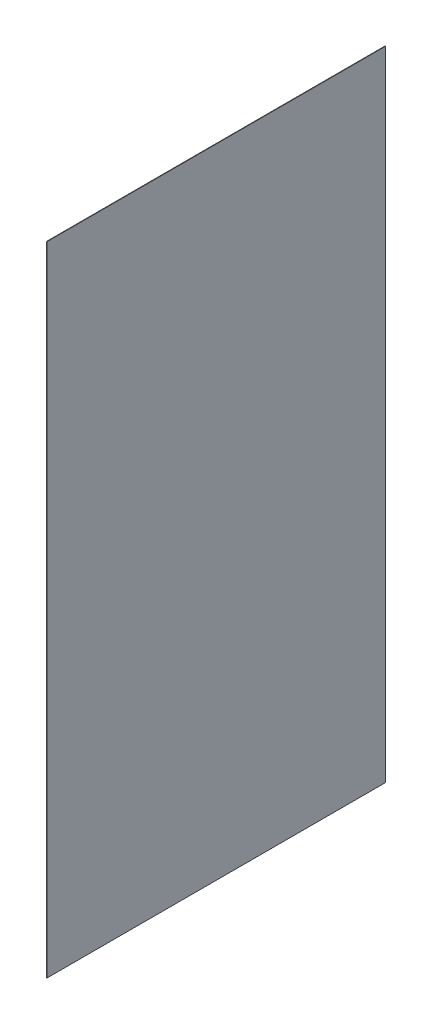
SolidWorks part; units mm, degrees
ref_plane "Front Plane" through (0, 0, 0) normal (0, 0, 1) x (1, 0, 0)
ref_plane "Top Plane" through (0, 0, 0) normal (0, 1, 0) x (1, 0, 0)
ref_plane "Right Plane" through (0, 0, 0) normal (1, 0, 0) x (0, 0, -1)
other "Configuration Table"
sketch "Sketch1" plane through (0, 0, 0) normal (0, 0, 1) x (1, 0, 0)
  line L1 (1337.5, 181.5) -> (1338.5, 181.5)
  line L2 (1337.5, 181.5) -> (1337.5, 1611)
  line L3 (1337.5, 1611) -> (1338.5, 1611)
  line L4 (1338.5, 181.5) -> (1338.5, 1611)
extrude "STORE_ic_yan_sag_1" add sketch "Sketch1" against normal blind 758.5 separate body
